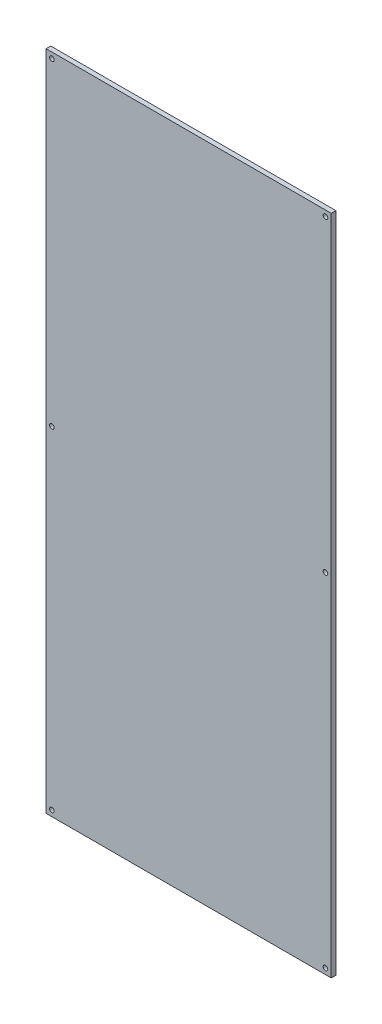
SolidWorks part; units mm, degrees
ref_plane "Plan de face" through (0, 0, 0) normal (0, 0, 1) x (1, 0, 0)
ref_plane "Plan de dessus" through (0, 0, 0) normal (0, 1, 0) x (1, 0, 0)
ref_plane "Plan de droite" through (0, 0, 0) normal (1, 0, 0) x (0, 0, -1)
sketch "Esquisse1" plane through (0, 0, 0) normal (0, 0, 1) x (1, 0, 0)
  line L1 (-39.7089, 30.4842) -> (83.7611, 30.4842)
  line L2 (-39.7089, 30.4842) -> (-39.7089, -256.3158)
  line L3 (-39.7089, -256.3158) -> (83.7611, -256.3158)
  line L4 (83.7611, 30.4842) -> (83.7611, -256.3158)
  circle A0 centre (-37.2089, 27.9842) radius 1
  circle A1 centre (81.2611, 27.9842) radius 1
  circle A2 centre (-37.2089, -253.8158) radius 1
  circle A3 centre (-37.2089, -109.9158) radius 1
  circle A4 centre (81.2611, -253.8158) radius 1
  circle A5 centre (81.2611, -105.4688) radius 1
  dimension "D3" = 2.5
  dimension "D1" = 123.47
  dimension "D2" = 286.8
  dimension "D4" = 2.5
  dimension "D5" = 2.5
  dimension "D6" = 2.5
  dimension "D7" = 2.5
  dimension "D8" = 2.5
  dimension "D9" = 2.5
  dimension "D10" = 2.5
  dimension "D11" = 2.5
  dimension "D12" = 2.5
  dimension "D13" = 146.4
extrude "Boss.-Extru.1" add sketch "Esquisse1" along normal blind 2
